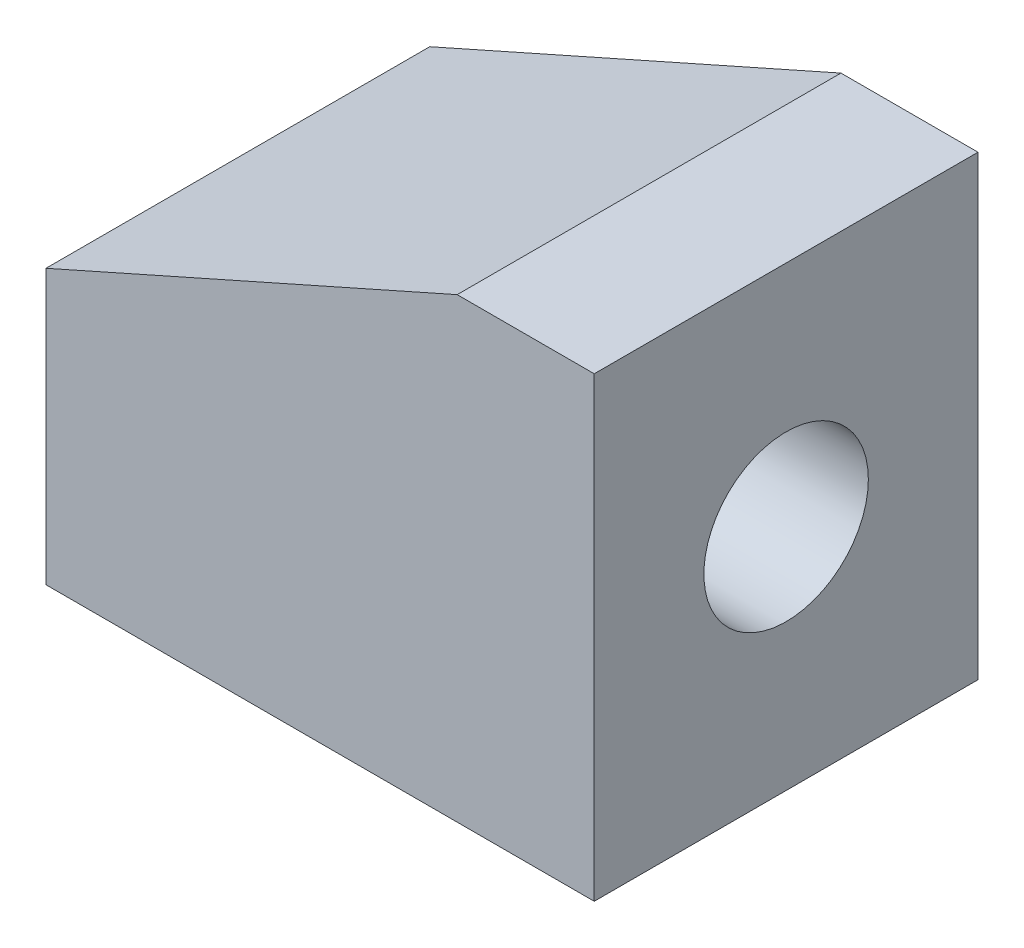
SolidWorks part; units mm, degrees
ref_plane "Ön Düzlem" through (0, 0, 0) normal (0, 0, 1) x (1, 0, 0)
ref_plane "Üst Düzlem" through (0, 0, 0) normal (0, 1, 0) x (1, 0, 0)
ref_plane "Sağ Düzlem" through (0, 0, 0) normal (1, 0, 0) x (0, 0, -1)
sketch "Çizim1" plane through (0, 0, 0) normal (0, 0, 1) x (1, 0, 0)
  line L0 (-81.5022, 17.1489) -> (-81.5022, -12.8511)
  line L1 (-81.5022, -12.8511) -> (-21.5022, -12.8511)
  line L2 (-21.5022, -12.8511) -> (-21.5022, 37.1489)
  line L3 (-21.5022, 37.1489) -> (-36.5022, 37.1489)
  line L4 (-36.5022, 37.1489) -> (-81.5022, 17.1489)
  dimension "D1" = 15
  dimension "D2" = 30
  dimension "D3" = 50
  dimension "D4" = 60
extrude "Yükseklik-Ekstrüzyon1" add sketch "Çizim1" along normal blind 42
sketch "Çizim2" plane through (-21.5022, 0, 0) normal (1, 0, 0) x (0, 0, -1)
  line L0 (-42, -12.8511) -> (0, -12.8511) construction
  line L1 (0, -12.8511) -> (0, 37.1489) construction
  circle A0 centre (-21, 12.1489) radius 9
  dimension "D1" = 18
  dimension "D2" = 25
  dimension "D3" = 21
extrude "Kes-Ekstrüzyon1" cut sketch "Çizim2" against normal blind 40
